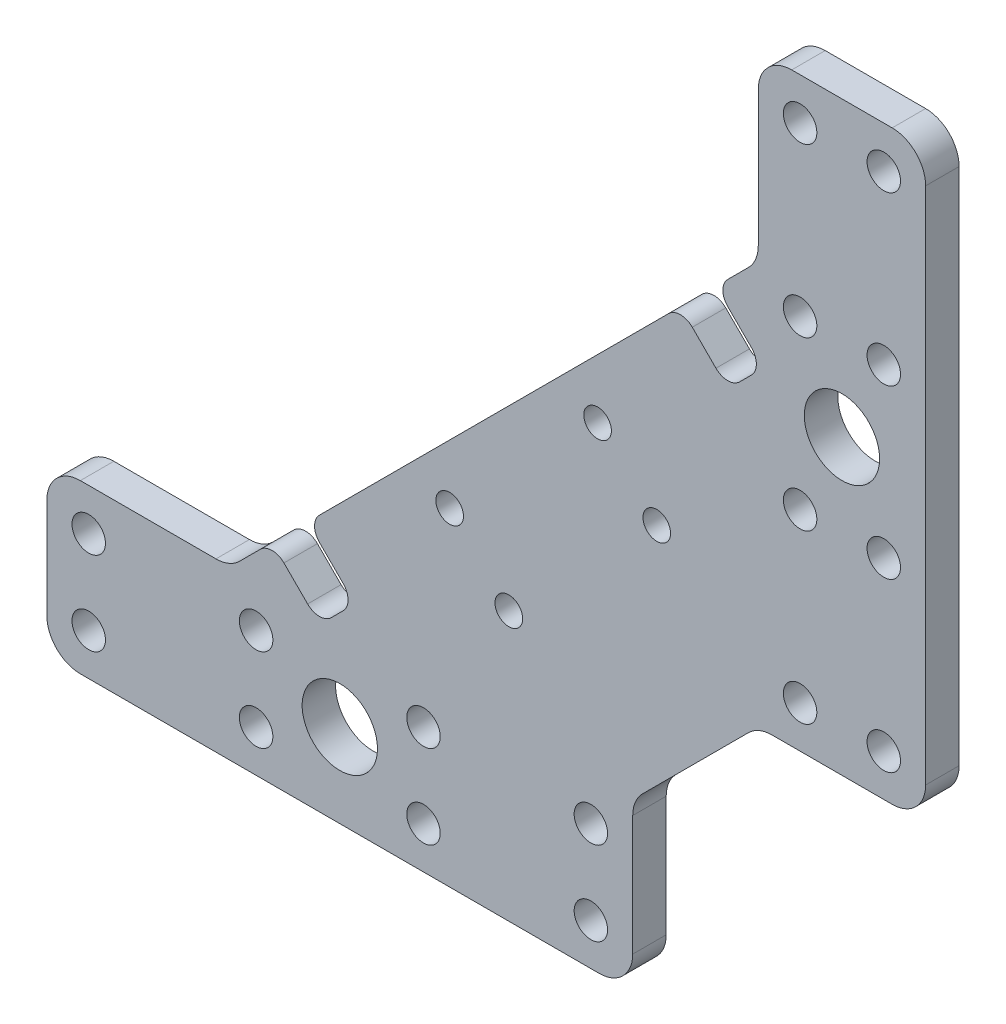
SolidWorks part; units mm, degrees
material "Thornel Mat VMA"
ref_plane "前视基准面" through (0, 0, 0) normal (0, 0, 1) x (1, 0, 0)
ref_plane "上视基准面" through (0, 0, 0) normal (0, 1, 0) x (1, 0, 0)
ref_plane "右视基准面" through (0, 0, 0) normal (1, 0, 0) x (0, 0, -1)
other "Configuration Table"
sketch "草图1" plane through (0, 0, 0) normal (0, 0, 1) x (1, 0, 0)
  line L0 (0, 0) -> (60, 0) construction
  line L1 (-10, -5) -> (10, -5) construction
  line L2 (-10, -5) -> (-10, 5) construction
  line L3 (-10, 5) -> (10, 5) construction
  line L4 (10, -5) -> (10, 5) construction
  line L5 (-10, -5) -> (10, 5) construction
  line L6 (-10, 5) -> (10, -5) construction
  line L7 (-30, -5) -> (30, -5) construction
  line L8 (-30, -5) -> (-30, 5) construction
  line L9 (-30, 5) -> (30, 5) construction
  line L10 (30, -5) -> (30, 5) construction
  line L11 (-30, -5) -> (30, 5) construction
  line L12 (-30, 5) -> (30, -5) construction
  line L13 (60, 0) -> (-62.4098, 122.4098) construction
  line L14 (50, 95) -> (70, 25) construction
  line L15 (55, -5) -> (65, -5) construction
  line L16 (55, -5) -> (55, 5) construction
  line L17 (55, 5) -> (65, 5) construction
  line L18 (65, -5) -> (65, 5) construction
  line L19 (55, -5) -> (65, 5) construction
  line L20 (55, 5) -> (65, -5) construction
  line L21 (-35, -10) -> (35, -10)
  line L22 (-35, -10) -> (-35, 10)
  line L23 (-35, 10) -> (35, 10)
  line L24 (35, -10) -> (35, 10)
  line L25 (-35, -10) -> (35, 10) construction
  line L26 (-35, 10) -> (35, -10) construction
  line L27 (70, 95) -> (50, 25) construction
  line L28 (55, 90) -> (65, 30) construction
  line L29 (65, 90) -> (55, 30) construction
  line L30 (65, 30) -> (55, 30) construction
  line L31 (55, 90) -> (55, 30) construction
  line L32 (65, 90) -> (55, 90) construction
  line L33 (65, 90) -> (65, 30) construction
  line L34 (55, 70) -> (65, 50) construction
  line L35 (65, 70) -> (55, 50) construction
  line L36 (65, 50) -> (55, 50) construction
  line L37 (55, 70) -> (55, 50) construction
  line L38 (65, 70) -> (55, 70) construction
  line L39 (65, 70) -> (65, 50) construction
  line L40 (70, 25) -> (50, 25)
  line L41 (50, 95) -> (50, 25)
  line L42 (70, 95) -> (50, 95)
  line L43 (70, 95) -> (70, 25)
  line L44 (35, 10) -> (50, 25)
  line L45 (20.1967, 22.1256) -> (13.1256, 29.1967) construction
  line L46 (50, 42.0294) -> (17.9706, 10)
  line L52 (20.1967, 22.1256) -> (37.8744, 39.8033) construction
  line L53 (50, 73.1421) -> (-13.1421, 10)
  line L54 (13.1256, 29.1967) -> (30.8033, 46.8744) construction
  line L55 (37.8744, 39.8033) -> (30.8033, 46.8744) construction
  line L56 (20.1967, 22.1256) -> (30.8033, 46.8744) construction
  line L57 (13.1256, 29.1967) -> (37.8744, 39.8033) construction
  circle A0 centre (30, 5) radius 2
  circle A1 centre (30, -5) radius 2
  circle A2 centre (10, -5) radius 2
  circle A3 centre (10, 5) radius 2
  circle A4 centre (-10, 5) radius 2
  circle A5 centre (-10, -5) radius 2
  circle A6 centre (-30, 5) radius 2
  circle A7 centre (-30, -5) radius 2
  circle A8 centre (0, 0) radius 4.5
  circle A9 centre (60, 60) radius 4.5
  circle A10 centre (65, 90) radius 2
  circle A11 centre (55, 90) radius 2
  circle A12 centre (65, 70) radius 2
  circle A13 centre (55, 70) radius 2
  circle A14 centre (55, 50) radius 2
  circle A15 centre (65, 50) radius 2
  circle A16 centre (65, 30) radius 2
  circle A17 centre (55, 30) radius 2
  circle A18 centre (30.8033, 46.8744) radius 1.65
  circle A19 centre (37.8744, 39.8033) radius 1.65
  circle A20 centre (13.1256, 29.1967) radius 1.65
  circle A21 centre (20.1967, 22.1256) radius 1.65
  point P0 (0, 0)
  point P6 (0, 0)
  point P53 (60, 60)
  point P54 (60, 60)
  point P59 (25.5, 34.5)
  point P60 (26.5, 33.5)
  dimension "D8" = 4
  dimension "D9" = 9
  dimension "D14" = 22
  dimension "D12" = 3.3
  dimension "D13" = 5
  dimension "D1" = 45
  dimension "D2" = 30
  dimension "D3" = 10
  dimension "D4" = 20
  dimension "D5" = 60
  dimension "D6" = 20
  dimension "D7" = 70
  dimension "D10" = 25
  dimension "D11" = 10
  dimension "D15" = 44.5
extrude "凸台-拉伸1" add sketch "草图1" along normal blind 4
fillet "圆角1" radius 4 10 edges at (35, 10, 2) (35, -10, 2) (-35, -10, 2) (50, 95, 2) (70, 95, 2) (70, 25, 2) (50, 25, 2) (-35, 10, 2) (50, 73.1421, 2) (-13.1421, 10, 2)
sketch "草图2" plane through (0, 0, 4) normal (0, 0, 1) x (1, 0, 0)
  line L0 (18.4289, 41.5711) -> (64.5659, -4.5659) construction
  line L1 (48.8284, 71.9706) -> (-11.9706, 11.1716) construction
  line L2 (-8.0876, 15.0546) -> (-3.8449, 19.2972)
  line L3 (-8.0876, 15.0546) -> (-2.4307, 9.3977)
  line L4 (-3.8449, 19.2972) -> (1.8119, 13.6403)
  line L5 (-2.4307, 9.3977) -> (1.8119, 13.6403)
  line L6 (44.9454, 68.0876) -> (40.7028, 63.8449)
  line L7 (44.9454, 68.0876) -> (50.6023, 62.4307)
  line L8 (50.6023, 62.4307) -> (46.3597, 58.1881)
  line L9 (40.7028, 63.8449) -> (46.3597, 58.1881)
  circle A0 centre (13.1256, 29.1967) radius 1.65 construction
  dimension "D1" = 6
  dimension "D2" = 19
  dimension "D3" = 8
extrude "切除-拉伸1" cut sketch "草图2" against normal blind 10
fillet "圆角2" radius 2 8 edges at (50.6023, 62.4307, 2) (46.3597, 58.1881, 2) (40.7028, 63.8449, 2) (-3.8449, 19.2972, 2) (1.8119, 13.6403, 2) (-2.4307, 9.3977, 2) (-8.0876, 15.0546, 2) (44.9454, 68.0876, 2)
